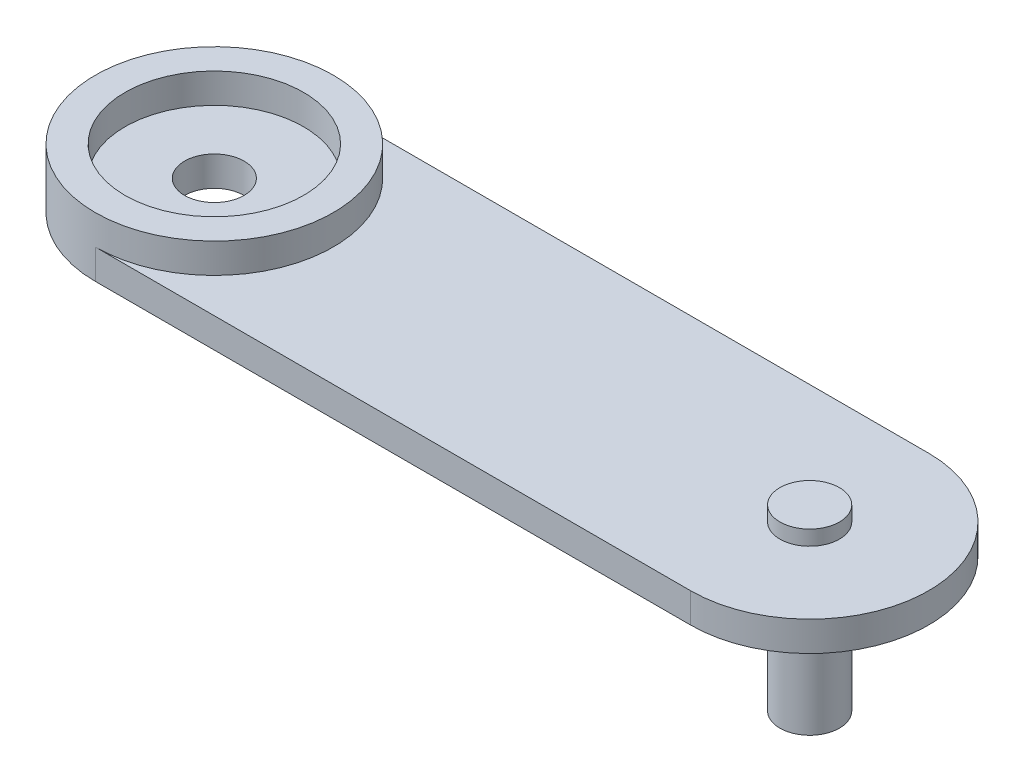
SolidWorks part; units mm, degrees
ref_plane "Front Plane" through (0, 0, 0) normal (0, 0, 1) x (1, 0, 0)
ref_plane "Top Plane" through (0, 0, 0) normal (0, 1, 0) x (1, 0, 0)
ref_plane "Right Plane" through (0, 0, 0) normal (1, 0, 0) x (0, 0, -1)
sketch "Sketch1" plane through (0, 0, 0) normal (0, 1, 0) x (1, 0, 0)
  line L1 (-200, 40) -> (0, 40)
  line L2 (-200, -40) -> (0, -40)
  arc A0 (0, -40) -> (0, 40) centre (0, 0) ccw
  arc A1 (-200, 40) -> (-200, -40) centre (-200, 0) ccw
  dimension "D1" = 80
  dimension "D2" = 80
  dimension "D3" = 200
extrude "Boss-Extrude1" add sketch "Sketch1" along normal blind 10
sketch "Sketch2" plane through (0, 10, 0) normal (0, 1, 0) x (1, 0, 0)
  circle A0 centre (-200, 0) radius 40
extrude "Boss-Extrude2" add sketch "Sketch2" along normal blind 10
sketch "Sketch3" plane through (0, 20, 0) normal (0, 1, 0) x (1, 0, 0)
  circle A0 centre (-200, 0) radius 30
  dimension "D1" = 60
extrude "Cut-Extrude1" cut sketch "Sketch3" against normal blind 10
sketch "Sketch4" plane through (0, 10, 0) normal (0, 1, 0) x (1, 0, 0)
  circle A0 centre (-200, 0) radius 10
  dimension "D1" = 20
extrude "Cut-Extrude2" cut sketch "Sketch4" against normal blind 10
sketch "Sketch5" plane through (0, 10, 0) normal (0, 1, 0) x (1, 0, 0)
  circle A0 centre (0, 0) radius 10
  dimension "D1" = 20
extrude "Boss-Extrude4" add sketch "Sketch5" along normal blind 5 and the other way blind 55 contours A0
